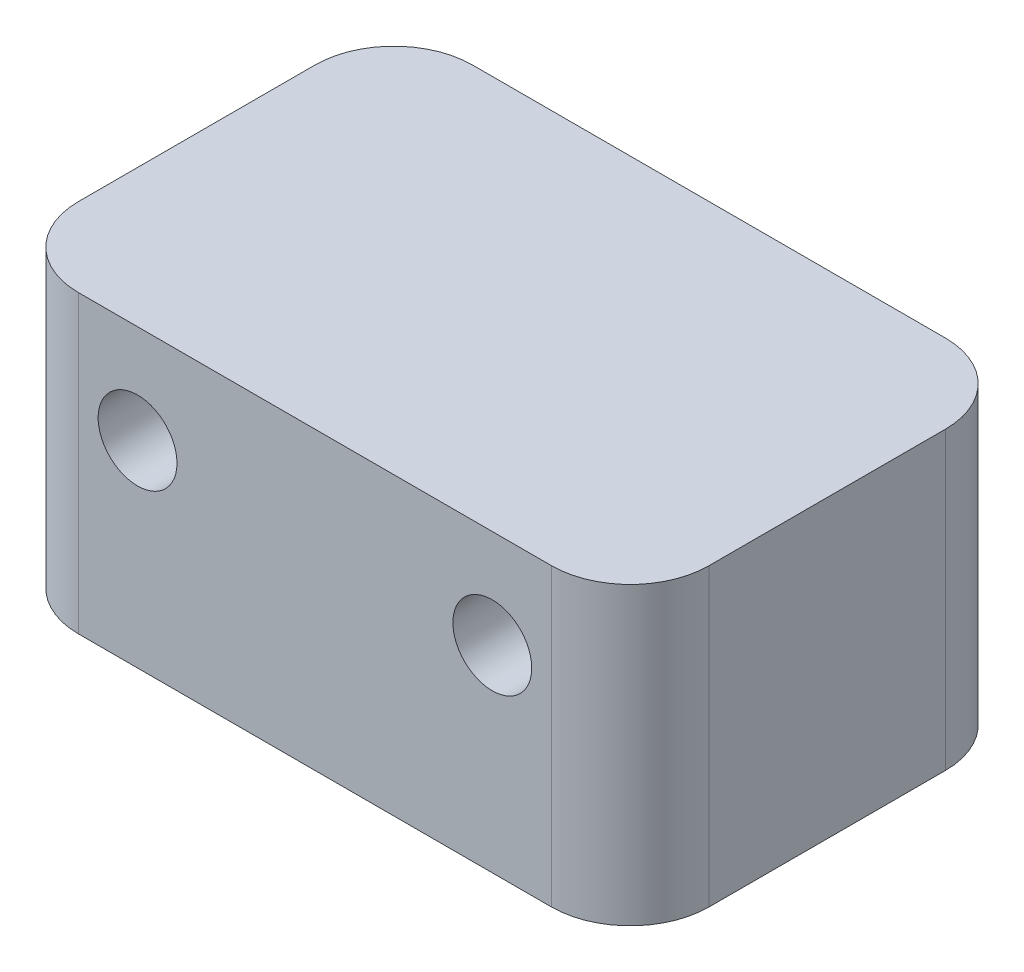
SolidWorks part; units mm, degrees
ref_plane "Plan de face" through (0, 0, 0) normal (0, 0, 1) x (1, 0, 0)
ref_plane "Plan de dessus" through (0, 0, 0) normal (0, 1, 0) x (1, 0, 0)
ref_plane "Plan de droite" through (0, 0, 0) normal (1, 0, 0) x (0, 0, -1)
sketch "Esquisse1" plane through (0, 0, 0) normal (0, 1, 0) x (1, 0, 0)
  line L0 (0, 0) -> (16, 0)
  line L1 (0, 0) -> (-16, 0)
  line L2 (-16, 0) -> (-16, 20)
  line L3 (-16, 20) -> (16, 20)
  line L4 (16, 20) -> (16, 0)
  dimension "D1" = 16
  dimension "D2" = 20
  dimension "D3" = 32
extrude "Boss.-Extru.1" add sketch "Esquisse1" along normal blind 15
fillet "Congé1" radius 4 4 edges at (-16, 7.5, -20) (16, 7.5, -20) (-16, 7.5, 0) (16, 7.5, 0)
sketch "Esquisse2" plane through (0, 0, 0) normal (0, -1, 0) x (1, 0, 0)
  line L0 (0, -20) -> (0, -10) construction
  line L1 (12, -20) -> (-12, -20) construction
  line L2 (0, -15) -> (-10, -15) construction
  line L3 (0, -15) -> (10, -15) construction
  line L4 (0, 0) -> (0, -5) construction
  line L5 (0, -5) -> (0, -15) construction
  circle A0 centre (-10, -15) radius 2
  circle A1 centre (10, -15) radius 2
  circle A2 centre (0, -5) radius 2
  dimension "D1" = 10
  dimension "D3" = 10
  dimension "D2" = 10
extrude "Enlèv. mat.-Extru.1" cut sketch "Esquisse2" against normal blind 12
sketch "Esquisse3" plane through (0, 0, 0) normal (0, 0, 1) x (1, 0, 0)
  line L0 (0, 0) -> (0, 10) construction
  line L1 (0, 10) -> (-9, 10) construction
  line L2 (0, 10) -> (9, 10) construction
  circle A0 centre (-9, 10) radius 2
  circle A1 centre (9, 10) radius 2
extrude "Enlèv. mat.-Extru.2" cut sketch "Esquisse3" against normal blind 12
